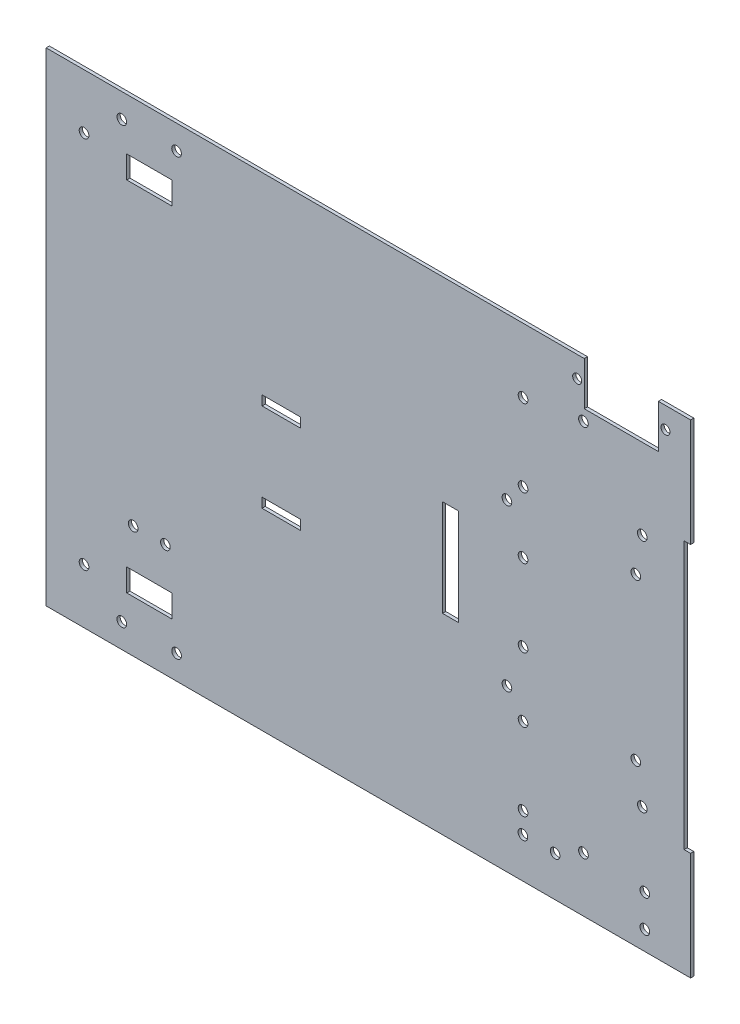
SolidWorks part; units mm, degrees
ref_plane "Front Plane" through (0, 0, 0) normal (0, 0, 1) x (1, 0, 0)
ref_plane "Top Plane" through (0, 0, 0) normal (0, 1, 0) x (1, 0, 0)
ref_plane "Right Plane" through (0, 0, 0) normal (1, 0, 0) x (0, 0, -1)
sketch "Sketch1" plane through (0, 0, 0) normal (0, 0, 1) x (1, 0, 0)
  line L1 (-100, 75) -> (100, 75)
  line L2 (-100, 75) -> (-100, -75)
  line L3 (-100, -75) -> (100, -75)
  line L4 (100, 75) -> (100, -75)
  line L5 (-100, 75) -> (100, -75) construction
  line L6 (-100, -75) -> (100, 75) construction
  point P0 (0, 0)
  dimension "D1" = 150
  dimension "D2" = 200
extrude "Boss-Extrude1" add sketch "Sketch1" along normal blind 1
sketch "Sketch2" plane through (0, 0, 1) normal (0, 0, 1) x (1, 0, 0)
  line L0 (-100, -75) -> (100, -75) construction
  line L1 (-75, -59) -> (-61, -59)
  line L2 (-75, -59) -> (-75, -52)
  line L3 (-75, -52) -> (-61, -52)
  line L4 (-61, -59) -> (-61, -52)
  line L5 (0, 0) -> (-128.0779, 0) construction
  line L6 (-100, 75) -> (-100, -75) construction
  line L7 (-75, 52) -> (-61, 52)
  line L8 (-61, 59) -> (-61, 52)
  line L9 (-75, 59) -> (-61, 59)
  line L10 (-75, 59) -> (-75, 52)
  line L12 (-33, -15.25) -> (-21, -15.25)
  line L13 (-33, -15.25) -> (-33, -12.25)
  line L14 (-33, -12.25) -> (-21, -12.25)
  line L15 (-21, -15.25) -> (-21, -12.25)
  line L19 (-68, -59) -> (-68, 77.2046) construction
  line L24 (-33, 12.25) -> (-21, 12.25)
  line L25 (-21, 15.25) -> (-21, 12.25)
  line L26 (-33, 15.25) -> (-21, 15.25)
  line L27 (-33, 15.25) -> (-33, 12.25)
  line L28 (100, 75) -> (-100, 75) construction
  line L33 (100, -75) -> (100, 75) construction
  line L34 (67, 75) -> (90, 75)
  line L35 (67, 75) -> (67, 61.5)
  line L36 (67, 61.5) -> (90, 61.5)
  line L37 (90, 75) -> (90, 61.5)
  line L38 (-100, -75) -> (100, -75) construction
  line L40 (100, 41.5) -> (98, 41.5)
  line L41 (100, 41.5) -> (100, -41.5)
  line L42 (100, -41.5) -> (98, -41.5)
  line L43 (98, 41.5) -> (98, -41.5)
  circle A0 centre (-76.53, -67.5) radius 1.5
  circle A1 centre (-59.53, -67.5) radius 1.5
  circle A3 centre (-59.53, 67.5) radius 1.5
  circle A4 centre (-76.53, 67.5) radius 1.5
  circle A5 centre (-73, -40) radius 1.5
  circle A6 centre (-63, -40) radius 1.5
  circle A7 centre (-88.2535, -58) radius 1.5
  circle A8 centre (66.7465, -58) radius 1.5
  circle A9 centre (66.7465, 58) radius 1.5
  circle A10 centre (-88.2535, 58) radius 1.5
  circle A13 centre (64.8, 68.5) radius 1.4
  circle A14 centre (92.2, 68.5) radius 1.4
  circle A15 centre (85, 36.5) radius 1.5
  circle A16 centre (85, -36.5) radius 1.5
  point P13 (-68, -59)
  point P32 (66.7465, 58)
  dimension "D3" = 3
  dimension "D9" = 2
  dimension "D13" = 12.25
  dimension "D14" = 155
  dimension "D17" = 10
  dimension "D18" = 2.2
  dimension "D22" = 73
  dimension "D1" = 39
  dimension "D2" = 7
  dimension "D4" = 1.47
  dimension "D5" = 7.5
  dimension "D6" = 12
  dimension "D7" = 16
  dimension "D8" = 25
  dimension "D10" = 2
  dimension "D11" = 12
  dimension "D12" = 12
  dimension "D15" = 13.5
  dimension "D16" = 23
  dimension "D19" = 2.2
  dimension "D20" = 6.5
  dimension "D21" = 6.5
  dimension "D23" = 38.5
  dimension "D24" = 15
  dimension "D25" = 15
  dimension "D26" = 2
  dimension "D27" = 5
  dimension "D28" = 5
extrude "Cut-Extrude1" cut sketch "Sketch2" against normal blind 1
sketch "Sketch3" plane through (0, 0, 1) normal (0, 0, 1) x (1, 0, 0)
  line L0 (-100, -75) -> (100, -75) construction
  line L1 (100, -75) -> (100, -41.5) construction
  line L2 (-33, -15.25) -> (-21, -15.25) construction
  line L3 (23, -15.49) -> (28, -15.49)
  line L4 (23, -15.49) -> (23, 14.51)
  line L5 (23, 14.51) -> (28, 14.51)
  line L6 (28, -15.49) -> (28, 14.51)
  line L7 (23, -15.49) -> (28, 14.51) construction
  line L8 (23, 14.51) -> (28, -15.49) construction
  line L9 (98, 41.5) -> (98, -41.5) construction
  circle A0 centre (85.8, -69.04) radius 1.5
  circle A1 centre (85.8, -59.04) radius 1.5
  circle A2 centre (57.96, -62.5) radius 1.5
  circle A3 centre (47.96, -62.5) radius 1.5
  point P12 (25.5, -0.49)
  dimension "D1" = 10
  dimension "D5" = 0
  dimension "D2" = 5.96
  dimension "D3" = 14.2
  dimension "D4" = 14.2
  dimension "D6" = 27.84
  dimension "D7" = 12.5
  dimension "D8" = 10
  dimension "D9" = 5
  dimension "D10" = 30
  dimension "D11" = 0.24
  dimension "D12" = 70
extrude "Cut-Extrude2" cut sketch "Sketch3" against normal blind 10
sketch "Sketch4" plane through (0, 0, 1) normal (0, 0, 1) x (1, 0, 0)
  line L0 (-100, 0) -> (98, 0) construction
  line L1 (-100, 75) -> (-100, -75) construction
  line L2 (98, 41.5) -> (98, -41.5) construction
  line L4 (98, 41.5) -> (98, -41.5) construction
  circle A0 centre (48, -12) radius 1.5
  circle A1 centre (48, -56.04) radius 1.5
  circle A2 centre (48, -32.04) radius 1.5
  circle A3 centre (48, 12) radius 1.5
  circle A4 centre (48, 31) radius 1.5
  circle A5 centre (48, 55) radius 1.5
  circle A6 centre (43, -25) radius 1.5
  circle A7 centre (83, -25) radius 1.5
  circle A8 centre (83, 25) radius 1.5
  circle A9 centre (43, 25) radius 1.5
  circle A10 centre (66.7465, 58) radius 1.5 construction
  circle A11 centre (85.8, -59.04) radius 1.5 construction
  point P26 (0, 0)
  point P29 (0, 0)
  point P34 (0, 0)
  point P35 (0, 0)
  dimension "D1" = 40
  dimension "D3" = 15
  dimension "D2" = 50
  dimension "D4" = 24
  dimension "D5" = 50
  dimension "D6" = 50
  dimension "D7" = 50
  dimension "D8" = 50
  dimension "D9" = 50
  dimension "D10" = 50
  dimension "D11" = 3
  dimension "D12" = 24
  dimension "D13" = 3
  dimension "D14" = 24
extrude "Cut-Extrude3" cut sketch "Sketch4" against normal blind 10
